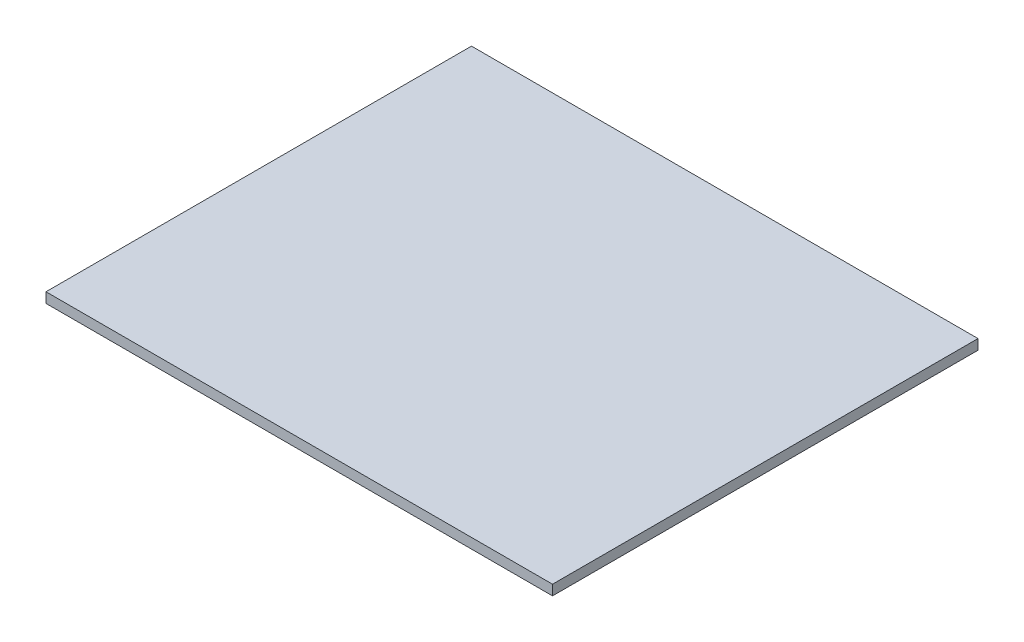
SolidWorks part; units mm, degrees
ref_plane "Front Plane" through (0, 0, 0) normal (0, 0, 1) x (1, 0, 0)
ref_plane "Top Plane" through (0, 0, 0) normal (0, 1, 0) x (1, 0, 0)
ref_plane "Right Plane" through (0, 0, 0) normal (1, 0, 0) x (0, 0, -1)
sketch "Sketch1" plane through (0, 0, 0) normal (0, 1, 0) x (1, 0, 0)
  line L1 (1250, -1050) -> (-1250, -1050)
  line L2 (1250, -1050) -> (1250, 1050)
  line L3 (1250, 1050) -> (-1250, 1050)
  line L4 (-1250, -1050) -> (-1250, 1050)
  line L5 (1250, -1050) -> (-1250, 1050) construction
  line L6 (1250, 1050) -> (-1250, -1050) construction
  point P0 (0, 0)
  dimension "D1" = 2500
  dimension "D2" = 2100
extrude "Boss-Extrude1" add sketch "Sketch1" along normal blind 50
sketch "Sketch2" plane through (0, 0, 0) normal (0, -1, 0) x (1, 0, 0)
  line L1 (375, -375) -> (-375, -375)
  line L2 (375, -375) -> (375, 375)
  line L3 (375, 375) -> (-375, 375)
  line L4 (-375, -375) -> (-375, 375)
  line L5 (375, -375) -> (-375, 375) construction
  line L6 (375, 375) -> (-375, -375) construction
  point P0 (0, 0)
  dimension "D1" = 750
  dimension "D2" = 750
extrude "Cut-Extrude1" cut sketch "Sketch2" against normal blind 10
